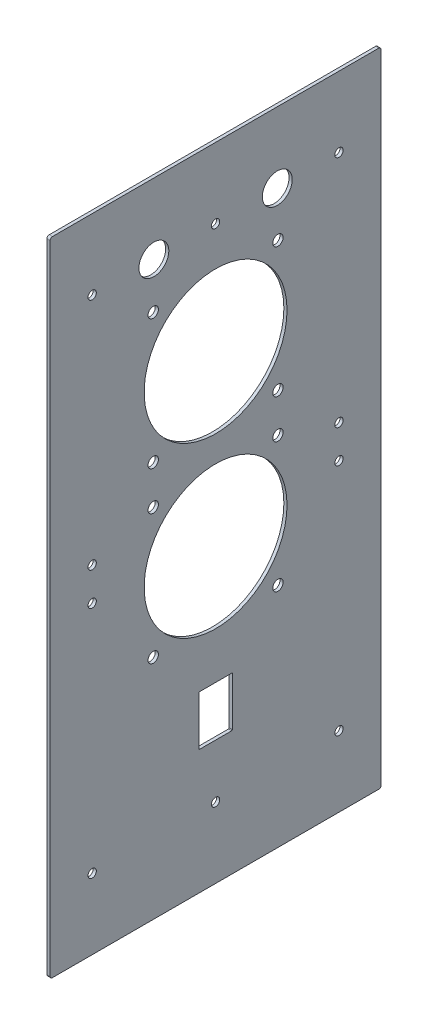
SolidWorks part; units mm, degrees
material "AISI 1020 Steel, Cold Rolled"
ref_plane "Front Plane" through (0, 0, 0) normal (0, 0, 1) x (1, 0, 0)
ref_plane "Top Plane" through (0, 0, 0) normal (0, 1, 0) x (1, 0, 0)
ref_plane "Right Plane" through (0, 0, 0) normal (1, 0, 0) x (0, 0, -1)
sketch "Sketch1" plane through (0, 0, 0) normal (1, 0, 0) x (0, 0, -1)
  line L0 (-62.8, -237.66) -> (62.8, -237.66) construction
  line L1 (-62.8, 9.9) -> (62.8, 9.9) construction
  line L2 (-62.8, -237.66) -> (62.8, -237.66) construction
  line L3 (-62.8, 9.9) -> (62.8, 9.9) construction
  line L4 (-63.943, 8.757) -> (-63.943, -236.517) construction
  line L5 (63.943, -236.517) -> (63.943, 8.757) construction
  line L6 (-62.8, 9.646) -> (62.8, 9.646)
  line L7 (63.689, -236.517) -> (63.689, 8.757)
  line L8 (-62.8, -237.406) -> (62.8, -237.406)
  line L9 (-63.689, 8.757) -> (-63.689, -236.517)
  arc A0 (63.943, 8.757) -> (62.8, 9.9) centre (62.8, 8.757) ccw construction
  arc A1 (62.8, -237.66) -> (63.943, -236.517) centre (62.8, -236.517) ccw construction
  arc A2 (-63.943, -236.517) -> (-62.8, -237.66) centre (-62.8, -236.517) ccw construction
  arc A3 (-62.8, 9.9) -> (-63.943, 8.757) centre (-62.8, 8.757) ccw construction
  arc A4 (63.943, 8.757) -> (62.8, 9.9) centre (62.8, 8.757) ccw construction
  arc A5 (62.8, -237.66) -> (63.943, -236.517) centre (62.8, -236.517) ccw construction
  arc A6 (-63.943, -236.517) -> (-62.8, -237.66) centre (-62.8, -236.517) ccw construction
  arc A7 (-62.8, 9.9) -> (-63.943, 8.757) centre (-62.8, 8.757) ccw construction
  arc A8 (63.689, 8.757) -> (62.8, 9.646) centre (62.8, 8.757) ccw
  arc A9 (62.8, -237.406) -> (63.689, -236.517) centre (62.8, -236.517) ccw
  arc A10 (-63.689, -236.517) -> (-62.8, -237.406) centre (-62.8, -236.517) ccw
  arc A11 (-62.8, 9.646) -> (-63.689, 8.757) centre (-62.8, 8.757) ccw
  dimension "D1" = 0.254
extrude "Boss-Extrude1" add sketch "Sketch1" along normal blind 1.22 contours L6 A11 L9 A10 L8 A9 L7 A8
sketch "Sketch2" plane through (0, 0, 0) normal (1, 0, 0) x (0, 0, -1)
  line L0 (0, 9.646) -> (0, -237.406) construction
  line L1 (-62.8, 9.646) -> (62.8, 9.646) construction
  line L2 (-62.8, -237.406) -> (62.8, -237.406) construction
  line L3 (0, -10.38) -> (0, 6.62) construction
  line L4 (-1.5, -10.38) -> (-1.5, 6.62)
  line L5 (1.5, -10.38) -> (1.5, 6.62)
  line L6 (0, -113.88) -> (80.3915, -113.88) construction
  line L7 (10, -10.38) -> (10, 6.62) construction
  line L8 (8.5, -10.38) -> (8.5, 6.62)
  line L9 (11.5, -10.38) -> (11.5, 6.62)
  line L10 (20, -10.38) -> (20, 6.62) construction
  line L11 (18.5, -10.38) -> (18.5, 6.62)
  line L12 (21.5, -10.38) -> (21.5, 6.62)
  line L13 (30, -10.38) -> (30, 6.62) construction
  line L14 (28.5, -10.38) -> (28.5, 6.62)
  line L15 (31.5, -10.38) -> (31.5, 6.62)
  line L16 (40, -10.38) -> (40, 6.62) construction
  line L17 (38.5, -10.38) -> (38.5, 6.62)
  line L18 (41.5, -10.38) -> (41.5, 6.62)
  line L19 (50, -10.38) -> (50, 6.62) construction
  line L20 (48.5, -10.38) -> (48.5, 6.62)
  line L21 (51.5, -10.38) -> (51.5, 6.62)
  line L22 (0, -10.38) -> (0, 6.62) construction
  line L23 (-1.5, -10.38) -> (-1.5, 6.62)
  line L24 (1.5, -10.38) -> (1.5, 6.62)
  line L25 (10, -10.38) -> (10, 6.62) construction
  line L26 (8.5, -10.38) -> (8.5, 6.62)
  line L27 (11.5, -10.38) -> (11.5, 6.62)
  line L28 (20, -10.38) -> (20, 6.62) construction
  line L29 (18.5, -10.38) -> (18.5, 6.62)
  line L30 (21.5, -10.38) -> (21.5, 6.62)
  line L31 (30, -10.38) -> (30, 6.62) construction
  line L32 (28.5, -10.38) -> (28.5, 6.62)
  line L33 (31.5, -10.38) -> (31.5, 6.62)
  line L34 (40, -10.38) -> (40, 6.62) construction
  line L35 (38.5, -10.38) -> (38.5, 6.62)
  line L36 (41.5, -10.38) -> (41.5, 6.62)
  line L37 (-10, -10.38) -> (-10, 6.62) construction
  line L38 (-11.5, -10.38) -> (-11.5, 6.62)
  line L39 (-8.5, -10.38) -> (-8.5, 6.62)
  line L40 (0, -10.38) -> (0, 6.62) construction
  line L41 (-1.5, -10.38) -> (-1.5, 6.62)
  line L42 (1.5, -10.38) -> (1.5, 6.62)
  line L43 (10, -10.38) -> (10, 6.62) construction
  line L44 (8.5, -10.38) -> (8.5, 6.62)
  line L45 (11.5, -10.38) -> (11.5, 6.62)
  line L46 (20, -10.38) -> (20, 6.62) construction
  line L47 (18.5, -10.38) -> (18.5, 6.62)
  line L48 (21.5, -10.38) -> (21.5, 6.62)
  line L49 (30, -10.38) -> (30, 6.62) construction
  line L50 (28.5, -10.38) -> (28.5, 6.62)
  line L51 (31.5, -10.38) -> (31.5, 6.62)
  line L52 (-20, -10.38) -> (-20, 6.62) construction
  line L53 (-21.5, -10.38) -> (-21.5, 6.62)
  line L54 (-18.5, -10.38) -> (-18.5, 6.62)
  line L55 (-10, -10.38) -> (-10, 6.62) construction
  line L56 (-11.5, -10.38) -> (-11.5, 6.62)
  line L57 (-8.5, -10.38) -> (-8.5, 6.62)
  line L58 (0, -10.38) -> (0, 6.62) construction
  line L59 (-1.5, -10.38) -> (-1.5, 6.62)
  line L60 (1.5, -10.38) -> (1.5, 6.62)
  line L61 (10, -10.38) -> (10, 6.62) construction
  line L62 (8.5, -10.38) -> (8.5, 6.62)
  line L63 (11.5, -10.38) -> (11.5, 6.62)
  line L64 (20, -10.38) -> (20, 6.62) construction
  line L65 (18.5, -10.38) -> (18.5, 6.62)
  line L66 (21.5, -10.38) -> (21.5, 6.62)
  line L67 (-30, -10.38) -> (-30, 6.62) construction
  line L68 (-31.5, -10.38) -> (-31.5, 6.62)
  line L69 (-28.5, -10.38) -> (-28.5, 6.62)
  line L70 (-20, -10.38) -> (-20, 6.62) construction
  line L71 (-21.5, -10.38) -> (-21.5, 6.62)
  line L72 (-18.5, -10.38) -> (-18.5, 6.62)
  line L73 (-10, -10.38) -> (-10, 6.62) construction
  line L74 (-11.5, -10.38) -> (-11.5, 6.62)
  line L75 (-8.5, -10.38) -> (-8.5, 6.62)
  line L76 (0, -10.38) -> (0, 6.62) construction
  line L77 (-1.5, -10.38) -> (-1.5, 6.62)
  line L78 (1.5, -10.38) -> (1.5, 6.62)
  line L79 (10, -10.38) -> (10, 6.62) construction
  line L80 (8.5, -10.38) -> (8.5, 6.62)
  line L81 (11.5, -10.38) -> (11.5, 6.62)
  line L82 (-40, -10.38) -> (-40, 6.62) construction
  line L83 (-41.5, -10.38) -> (-41.5, 6.62)
  line L84 (-38.5, -10.38) -> (-38.5, 6.62)
  line L85 (-30, -10.38) -> (-30, 6.62) construction
  line L86 (-31.5, -10.38) -> (-31.5, 6.62)
  line L87 (-28.5, -10.38) -> (-28.5, 6.62)
  line L88 (-20, -10.38) -> (-20, 6.62) construction
  line L89 (-21.5, -10.38) -> (-21.5, 6.62)
  line L90 (-18.5, -10.38) -> (-18.5, 6.62)
  line L91 (-10, -10.38) -> (-10, 6.62) construction
  line L92 (-11.5, -10.38) -> (-11.5, 6.62)
  line L93 (-8.5, -10.38) -> (-8.5, 6.62)
  line L94 (0, -10.38) -> (0, 6.62) construction
  line L95 (-1.5, -10.38) -> (-1.5, 6.62)
  line L96 (1.5, -10.38) -> (1.5, 6.62)
  line L97 (-10, -10.38) -> (-10, 6.62) construction
  line L98 (-11.5, -10.38) -> (-11.5, 6.62)
  line L99 (-8.5, -10.38) -> (-8.5, 6.62)
  line L100 (-20, -10.38) -> (-20, 6.62) construction
  line L101 (-21.5, -10.38) -> (-21.5, 6.62)
  line L102 (-18.5, -10.38) -> (-18.5, 6.62)
  line L103 (-30, -10.38) -> (-30, 6.62) construction
  line L104 (-31.5, -10.38) -> (-31.5, 6.62)
  line L105 (-28.5, -10.38) -> (-28.5, 6.62)
  line L106 (-40, -10.38) -> (-40, 6.62) construction
  line L107 (-41.5, -10.38) -> (-41.5, 6.62)
  line L108 (-38.5, -10.38) -> (-38.5, 6.62)
  line L109 (-50, -10.38) -> (-50, 6.62) construction
  line L110 (-51.5, -10.38) -> (-51.5, 6.62)
  line L111 (-48.5, -10.38) -> (-48.5, 6.62)
  line L112 (0, -217.38) -> (0, -234.38) construction
  line L113 (-1.5, -217.38) -> (-1.5, -234.38)
  line L114 (1.5, -217.38) -> (1.5, -234.38)
  line L115 (10, -217.38) -> (10, -234.38) construction
  line L116 (8.5, -217.38) -> (8.5, -234.38)
  line L117 (11.5, -217.38) -> (11.5, -234.38)
  line L118 (20, -217.38) -> (20, -234.38) construction
  line L119 (18.5, -217.38) -> (18.5, -234.38)
  line L120 (21.5, -217.38) -> (21.5, -234.38)
  line L121 (30, -217.38) -> (30, -234.38) construction
  line L122 (28.5, -217.38) -> (28.5, -234.38)
  line L123 (31.5, -217.38) -> (31.5, -234.38)
  line L124 (40, -217.38) -> (40, -234.38) construction
  line L125 (38.5, -217.38) -> (38.5, -234.38)
  line L126 (41.5, -217.38) -> (41.5, -234.38)
  line L127 (50, -217.38) -> (50, -234.38) construction
  line L128 (48.5, -217.38) -> (48.5, -234.38)
  line L129 (51.5, -217.38) -> (51.5, -234.38)
  line L130 (0, -217.38) -> (0, -234.38) construction
  line L131 (-1.5, -217.38) -> (-1.5, -234.38)
  line L132 (1.5, -217.38) -> (1.5, -234.38)
  line L133 (10, -217.38) -> (10, -234.38) construction
  line L134 (8.5, -217.38) -> (8.5, -234.38)
  line L135 (11.5, -217.38) -> (11.5, -234.38)
  line L136 (20, -217.38) -> (20, -234.38) construction
  line L137 (18.5, -217.38) -> (18.5, -234.38)
  line L138 (21.5, -217.38) -> (21.5, -234.38)
  line L139 (30, -217.38) -> (30, -234.38) construction
  line L140 (28.5, -217.38) -> (28.5, -234.38)
  line L141 (31.5, -217.38) -> (31.5, -234.38)
  line L142 (40, -217.38) -> (40, -234.38) construction
  line L143 (38.5, -217.38) -> (38.5, -234.38)
  line L144 (41.5, -217.38) -> (41.5, -234.38)
  line L145 (-10, -217.38) -> (-10, -234.38) construction
  line L146 (-11.5, -217.38) -> (-11.5, -234.38)
  line L147 (-8.5, -217.38) -> (-8.5, -234.38)
  line L148 (0, -217.38) -> (0, -234.38) construction
  line L149 (-1.5, -217.38) -> (-1.5, -234.38)
  line L150 (1.5, -217.38) -> (1.5, -234.38)
  line L151 (10, -217.38) -> (10, -234.38) construction
  line L152 (8.5, -217.38) -> (8.5, -234.38)
  line L153 (11.5, -217.38) -> (11.5, -234.38)
  line L154 (20, -217.38) -> (20, -234.38) construction
  line L155 (18.5, -217.38) -> (18.5, -234.38)
  line L156 (21.5, -217.38) -> (21.5, -234.38)
  line L157 (30, -217.38) -> (30, -234.38) construction
  line L158 (28.5, -217.38) -> (28.5, -234.38)
  line L159 (31.5, -217.38) -> (31.5, -234.38)
  line L160 (-20, -217.38) -> (-20, -234.38) construction
  line L161 (-21.5, -217.38) -> (-21.5, -234.38)
  line L162 (-18.5, -217.38) -> (-18.5, -234.38)
  line L163 (-10, -217.38) -> (-10, -234.38) construction
  line L164 (-11.5, -217.38) -> (-11.5, -234.38)
  line L165 (-8.5, -217.38) -> (-8.5, -234.38)
  line L166 (0, -217.38) -> (0, -234.38) construction
  line L167 (-1.5, -217.38) -> (-1.5, -234.38)
  line L168 (1.5, -217.38) -> (1.5, -234.38)
  line L169 (10, -217.38) -> (10, -234.38) construction
  line L170 (8.5, -217.38) -> (8.5, -234.38)
  line L171 (11.5, -217.38) -> (11.5, -234.38)
  line L172 (20, -217.38) -> (20, -234.38) construction
  line L173 (18.5, -217.38) -> (18.5, -234.38)
  line L174 (21.5, -217.38) -> (21.5, -234.38)
  line L175 (-30, -217.38) -> (-30, -234.38) construction
  line L176 (-31.5, -217.38) -> (-31.5, -234.38)
  line L177 (-28.5, -217.38) -> (-28.5, -234.38)
  line L178 (-20, -217.38) -> (-20, -234.38) construction
  line L179 (-21.5, -217.38) -> (-21.5, -234.38)
  line L180 (-18.5, -217.38) -> (-18.5, -234.38)
  line L181 (-10, -217.38) -> (-10, -234.38) construction
  line L182 (-11.5, -217.38) -> (-11.5, -234.38)
  line L183 (-8.5, -217.38) -> (-8.5, -234.38)
  line L184 (0, -217.38) -> (0, -234.38) construction
  line L185 (-1.5, -217.38) -> (-1.5, -234.38)
  line L186 (1.5, -217.38) -> (1.5, -234.38)
  line L187 (10, -217.38) -> (10, -234.38) construction
  line L188 (8.5, -217.38) -> (8.5, -234.38)
  line L189 (11.5, -217.38) -> (11.5, -234.38)
  line L190 (-40, -217.38) -> (-40, -234.38) construction
  line L191 (-41.5, -217.38) -> (-41.5, -234.38)
  line L192 (-38.5, -217.38) -> (-38.5, -234.38)
  line L193 (-30, -217.38) -> (-30, -234.38) construction
  line L194 (-31.5, -217.38) -> (-31.5, -234.38)
  line L195 (-28.5, -217.38) -> (-28.5, -234.38)
  line L196 (-20, -217.38) -> (-20, -234.38) construction
  line L197 (-21.5, -217.38) -> (-21.5, -234.38)
  line L198 (-18.5, -217.38) -> (-18.5, -234.38)
  line L199 (-10, -217.38) -> (-10, -234.38) construction
  line L200 (-11.5, -217.38) -> (-11.5, -234.38)
  line L201 (-8.5, -217.38) -> (-8.5, -234.38)
  line L202 (0, -217.38) -> (0, -234.38) construction
  line L203 (-1.5, -217.38) -> (-1.5, -234.38)
  line L204 (1.5, -217.38) -> (1.5, -234.38)
  line L205 (-10, -217.38) -> (-10, -234.38) construction
  line L206 (-11.5, -217.38) -> (-11.5, -234.38)
  line L207 (-8.5, -217.38) -> (-8.5, -234.38)
  line L208 (-20, -217.38) -> (-20, -234.38) construction
  line L209 (-21.5, -217.38) -> (-21.5, -234.38)
  line L210 (-18.5, -217.38) -> (-18.5, -234.38)
  line L211 (-30, -217.38) -> (-30, -234.38) construction
  line L212 (-31.5, -217.38) -> (-31.5, -234.38)
  line L213 (-28.5, -217.38) -> (-28.5, -234.38)
  line L214 (-40, -217.38) -> (-40, -234.38) construction
  line L215 (-41.5, -217.38) -> (-41.5, -234.38)
  line L216 (-38.5, -217.38) -> (-38.5, -234.38)
  line L217 (-50, -217.38) -> (-50, -234.38) construction
  line L218 (-51.5, -217.38) -> (-51.5, -234.38)
  line L219 (-48.5, -217.38) -> (-48.5, -234.38)
  arc A0 (-1.5, -10.38) -> (1.5, -10.38) centre (0, -10.38) ccw
  arc A1 (1.5, 6.62) -> (-1.5, 6.62) centre (0, 6.62) ccw
  arc A2 (8.5, -10.38) -> (11.5, -10.38) centre (10, -10.38) ccw
  arc A3 (11.5, 6.62) -> (8.5, 6.62) centre (10, 6.62) ccw
  arc A4 (18.5, -10.38) -> (21.5, -10.38) centre (20, -10.38) ccw
  arc A5 (21.5, 6.62) -> (18.5, 6.62) centre (20, 6.62) ccw
  arc A6 (28.5, -10.38) -> (31.5, -10.38) centre (30, -10.38) ccw
  arc A7 (31.5, 6.62) -> (28.5, 6.62) centre (30, 6.62) ccw
  arc A8 (38.5, -10.38) -> (41.5, -10.38) centre (40, -10.38) ccw
  arc A9 (41.5, 6.62) -> (38.5, 6.62) centre (40, 6.62) ccw
  arc A10 (48.5, -10.38) -> (51.5, -10.38) centre (50, -10.38) ccw
  arc A11 (51.5, 6.62) -> (48.5, 6.62) centre (50, 6.62) ccw
  arc A12 (-1.5, -10.38) -> (1.5, -10.38) centre (0, -10.38) ccw
  arc A13 (1.5, 6.62) -> (-1.5, 6.62) centre (0, 6.62) ccw
  arc A14 (8.5, -10.38) -> (11.5, -10.38) centre (10, -10.38) ccw
  arc A15 (11.5, 6.62) -> (8.5, 6.62) centre (10, 6.62) ccw
  arc A16 (18.5, -10.38) -> (21.5, -10.38) centre (20, -10.38) ccw
  arc A17 (21.5, 6.62) -> (18.5, 6.62) centre (20, 6.62) ccw
  arc A18 (28.5, -10.38) -> (31.5, -10.38) centre (30, -10.38) ccw
  arc A19 (31.5, 6.62) -> (28.5, 6.62) centre (30, 6.62) ccw
  arc A20 (38.5, -10.38) -> (41.5, -10.38) centre (40, -10.38) ccw
  arc A21 (41.5, 6.62) -> (38.5, 6.62) centre (40, 6.62) ccw
  arc A22 (-11.5, -10.38) -> (-8.5, -10.38) centre (-10, -10.38) ccw
  arc A23 (-8.5, 6.62) -> (-11.5, 6.62) centre (-10, 6.62) ccw
  arc A24 (-1.5, -10.38) -> (1.5, -10.38) centre (0, -10.38) ccw
  arc A25 (1.5, 6.62) -> (-1.5, 6.62) centre (0, 6.62) ccw
  arc A26 (8.5, -10.38) -> (11.5, -10.38) centre (10, -10.38) ccw
  arc A27 (11.5, 6.62) -> (8.5, 6.62) centre (10, 6.62) ccw
  arc A28 (18.5, -10.38) -> (21.5, -10.38) centre (20, -10.38) ccw
  arc A29 (21.5, 6.62) -> (18.5, 6.62) centre (20, 6.62) ccw
  arc A30 (28.5, -10.38) -> (31.5, -10.38) centre (30, -10.38) ccw
  arc A31 (31.5, 6.62) -> (28.5, 6.62) centre (30, 6.62) ccw
  arc A32 (-21.5, -10.38) -> (-18.5, -10.38) centre (-20, -10.38) ccw
  arc A33 (-18.5, 6.62) -> (-21.5, 6.62) centre (-20, 6.62) ccw
  arc A34 (-11.5, -10.38) -> (-8.5, -10.38) centre (-10, -10.38) ccw
  arc A35 (-8.5, 6.62) -> (-11.5, 6.62) centre (-10, 6.62) ccw
  arc A36 (-1.5, -10.38) -> (1.5, -10.38) centre (0, -10.38) ccw
  arc A37 (1.5, 6.62) -> (-1.5, 6.62) centre (0, 6.62) ccw
  arc A38 (8.5, -10.38) -> (11.5, -10.38) centre (10, -10.38) ccw
  arc A39 (11.5, 6.62) -> (8.5, 6.62) centre (10, 6.62) ccw
  arc A40 (18.5, -10.38) -> (21.5, -10.38) centre (20, -10.38) ccw
  arc A41 (21.5, 6.62) -> (18.5, 6.62) centre (20, 6.62) ccw
  arc A42 (-31.5, -10.38) -> (-28.5, -10.38) centre (-30, -10.38) ccw
  arc A43 (-28.5, 6.62) -> (-31.5, 6.62) centre (-30, 6.62) ccw
  arc A44 (-21.5, -10.38) -> (-18.5, -10.38) centre (-20, -10.38) ccw
  arc A45 (-18.5, 6.62) -> (-21.5, 6.62) centre (-20, 6.62) ccw
  arc A46 (-11.5, -10.38) -> (-8.5, -10.38) centre (-10, -10.38) ccw
  arc A47 (-8.5, 6.62) -> (-11.5, 6.62) centre (-10, 6.62) ccw
  arc A48 (-1.5, -10.38) -> (1.5, -10.38) centre (0, -10.38) ccw
  arc A49 (1.5, 6.62) -> (-1.5, 6.62) centre (0, 6.62) ccw
  arc A50 (8.5, -10.38) -> (11.5, -10.38) centre (10, -10.38) ccw
  arc A51 (11.5, 6.62) -> (8.5, 6.62) centre (10, 6.62) ccw
  arc A52 (-41.5, -10.38) -> (-38.5, -10.38) centre (-40, -10.38) ccw
  arc A53 (-38.5, 6.62) -> (-41.5, 6.62) centre (-40, 6.62) ccw
  arc A54 (-31.5, -10.38) -> (-28.5, -10.38) centre (-30, -10.38) ccw
  arc A55 (-28.5, 6.62) -> (-31.5, 6.62) centre (-30, 6.62) ccw
  arc A56 (-21.5, -10.38) -> (-18.5, -10.38) centre (-20, -10.38) ccw
  arc A57 (-18.5, 6.62) -> (-21.5, 6.62) centre (-20, 6.62) ccw
  arc A58 (-11.5, -10.38) -> (-8.5, -10.38) centre (-10, -10.38) ccw
  arc A59 (-8.5, 6.62) -> (-11.5, 6.62) centre (-10, 6.62) ccw
  arc A60 (-1.5, -10.38) -> (1.5, -10.38) centre (0, -10.38) ccw
  arc A61 (1.5, 6.62) -> (-1.5, 6.62) centre (0, 6.62) ccw
  arc A62 (-11.5, -10.38) -> (-8.5, -10.38) centre (-10, -10.38) ccw
  arc A63 (-8.5, 6.62) -> (-11.5, 6.62) centre (-10, 6.62) ccw
  arc A64 (-21.5, -10.38) -> (-18.5, -10.38) centre (-20, -10.38) ccw
  arc A65 (-18.5, 6.62) -> (-21.5, 6.62) centre (-20, 6.62) ccw
  arc A66 (-31.5, -10.38) -> (-28.5, -10.38) centre (-30, -10.38) ccw
  arc A67 (-28.5, 6.62) -> (-31.5, 6.62) centre (-30, 6.62) ccw
  arc A68 (-41.5, -10.38) -> (-38.5, -10.38) centre (-40, -10.38) ccw
  arc A69 (-38.5, 6.62) -> (-41.5, 6.62) centre (-40, 6.62) ccw
  arc A70 (-51.5, -10.38) -> (-48.5, -10.38) centre (-50, -10.38) ccw
  arc A71 (-48.5, 6.62) -> (-51.5, 6.62) centre (-50, 6.62) ccw
  arc A72 (-1.5, -217.38) -> (1.5, -217.38) centre (0, -217.38) cw
  arc A73 (1.5, -234.38) -> (-1.5, -234.38) centre (0, -234.38) cw
  arc A74 (8.5, -217.38) -> (11.5, -217.38) centre (10, -217.38) cw
  arc A75 (11.5, -234.38) -> (8.5, -234.38) centre (10, -234.38) cw
  arc A76 (18.5, -217.38) -> (21.5, -217.38) centre (20, -217.38) cw
  arc A77 (21.5, -234.38) -> (18.5, -234.38) centre (20, -234.38) cw
  arc A78 (28.5, -217.38) -> (31.5, -217.38) centre (30, -217.38) cw
  arc A79 (31.5, -234.38) -> (28.5, -234.38) centre (30, -234.38) cw
  arc A80 (38.5, -217.38) -> (41.5, -217.38) centre (40, -217.38) cw
  arc A81 (41.5, -234.38) -> (38.5, -234.38) centre (40, -234.38) cw
  arc A82 (48.5, -217.38) -> (51.5, -217.38) centre (50, -217.38) cw
  arc A83 (51.5, -234.38) -> (48.5, -234.38) centre (50, -234.38) cw
  arc A84 (-1.5, -217.38) -> (1.5, -217.38) centre (0, -217.38) cw
  arc A85 (1.5, -234.38) -> (-1.5, -234.38) centre (0, -234.38) cw
  arc A86 (8.5, -217.38) -> (11.5, -217.38) centre (10, -217.38) cw
  arc A87 (11.5, -234.38) -> (8.5, -234.38) centre (10, -234.38) cw
  arc A88 (18.5, -217.38) -> (21.5, -217.38) centre (20, -217.38) cw
  arc A89 (21.5, -234.38) -> (18.5, -234.38) centre (20, -234.38) cw
  arc A90 (28.5, -217.38) -> (31.5, -217.38) centre (30, -217.38) cw
  arc A91 (31.5, -234.38) -> (28.5, -234.38) centre (30, -234.38) cw
  arc A92 (38.5, -217.38) -> (41.5, -217.38) centre (40, -217.38) cw
  arc A93 (41.5, -234.38) -> (38.5, -234.38) centre (40, -234.38) cw
  arc A94 (-11.5, -217.38) -> (-8.5, -217.38) centre (-10, -217.38) cw
  arc A95 (-8.5, -234.38) -> (-11.5, -234.38) centre (-10, -234.38) cw
  arc A96 (-1.5, -217.38) -> (1.5, -217.38) centre (0, -217.38) cw
  arc A97 (1.5, -234.38) -> (-1.5, -234.38) centre (0, -234.38) cw
  arc A98 (8.5, -217.38) -> (11.5, -217.38) centre (10, -217.38) cw
  arc A99 (11.5, -234.38) -> (8.5, -234.38) centre (10, -234.38) cw
  arc A100 (18.5, -217.38) -> (21.5, -217.38) centre (20, -217.38) cw
  arc A101 (21.5, -234.38) -> (18.5, -234.38) centre (20, -234.38) cw
  arc A102 (28.5, -217.38) -> (31.5, -217.38) centre (30, -217.38) cw
  arc A103 (31.5, -234.38) -> (28.5, -234.38) centre (30, -234.38) cw
  arc A104 (-21.5, -217.38) -> (-18.5, -217.38) centre (-20, -217.38) cw
  arc A105 (-18.5, -234.38) -> (-21.5, -234.38) centre (-20, -234.38) cw
  arc A106 (-11.5, -217.38) -> (-8.5, -217.38) centre (-10, -217.38) cw
  arc A107 (-8.5, -234.38) -> (-11.5, -234.38) centre (-10, -234.38) cw
  arc A108 (-1.5, -217.38) -> (1.5, -217.38) centre (0, -217.38) cw
  arc A109 (1.5, -234.38) -> (-1.5, -234.38) centre (0, -234.38) cw
  arc A110 (8.5, -217.38) -> (11.5, -217.38) centre (10, -217.38) cw
  arc A111 (11.5, -234.38) -> (8.5, -234.38) centre (10, -234.38) cw
  arc A112 (18.5, -217.38) -> (21.5, -217.38) centre (20, -217.38) cw
  arc A113 (21.5, -234.38) -> (18.5, -234.38) centre (20, -234.38) cw
  arc A114 (-31.5, -217.38) -> (-28.5, -217.38) centre (-30, -217.38) cw
  arc A115 (-28.5, -234.38) -> (-31.5, -234.38) centre (-30, -234.38) cw
  arc A116 (-21.5, -217.38) -> (-18.5, -217.38) centre (-20, -217.38) cw
  arc A117 (-18.5, -234.38) -> (-21.5, -234.38) centre (-20, -234.38) cw
  arc A118 (-11.5, -217.38) -> (-8.5, -217.38) centre (-10, -217.38) cw
  arc A119 (-8.5, -234.38) -> (-11.5, -234.38) centre (-10, -234.38) cw
  arc A120 (-1.5, -217.38) -> (1.5, -217.38) centre (0, -217.38) cw
  arc A121 (1.5, -234.38) -> (-1.5, -234.38) centre (0, -234.38) cw
  arc A122 (8.5, -217.38) -> (11.5, -217.38) centre (10, -217.38) cw
  arc A123 (11.5, -234.38) -> (8.5, -234.38) centre (10, -234.38) cw
  arc A124 (-41.5, -217.38) -> (-38.5, -217.38) centre (-40, -217.38) cw
  arc A125 (-38.5, -234.38) -> (-41.5, -234.38) centre (-40, -234.38) cw
  arc A126 (-31.5, -217.38) -> (-28.5, -217.38) centre (-30, -217.38) cw
  arc A127 (-28.5, -234.38) -> (-31.5, -234.38) centre (-30, -234.38) cw
  arc A128 (-21.5, -217.38) -> (-18.5, -217.38) centre (-20, -217.38) cw
  arc A129 (-18.5, -234.38) -> (-21.5, -234.38) centre (-20, -234.38) cw
  arc A130 (-11.5, -217.38) -> (-8.5, -217.38) centre (-10, -217.38) cw
  arc A131 (-8.5, -234.38) -> (-11.5, -234.38) centre (-10, -234.38) cw
  arc A132 (-1.5, -217.38) -> (1.5, -217.38) centre (0, -217.38) cw
  arc A133 (1.5, -234.38) -> (-1.5, -234.38) centre (0, -234.38) cw
  arc A134 (-11.5, -217.38) -> (-8.5, -217.38) centre (-10, -217.38) cw
  arc A135 (-8.5, -234.38) -> (-11.5, -234.38) centre (-10, -234.38) cw
  arc A136 (-21.5, -217.38) -> (-18.5, -217.38) centre (-20, -217.38) cw
  arc A137 (-18.5, -234.38) -> (-21.5, -234.38) centre (-20, -234.38) cw
  arc A138 (-31.5, -217.38) -> (-28.5, -217.38) centre (-30, -217.38) cw
  arc A139 (-28.5, -234.38) -> (-31.5, -234.38) centre (-30, -234.38) cw
  arc A140 (-41.5, -217.38) -> (-38.5, -217.38) centre (-40, -217.38) cw
  arc A141 (-38.5, -234.38) -> (-41.5, -234.38) centre (-40, -234.38) cw
  arc A142 (-51.5, -217.38) -> (-48.5, -217.38) centre (-50, -217.38) cw
  arc A143 (-48.5, -234.38) -> (-51.5, -234.38) centre (-50, -234.38) cw
  point P6 (0, -1.88)
  point P16 (0, -225.88)
  point P20 (10, -1.88)
  point P27 (20, -1.88)
  point P34 (30, -1.88)
  point P41 (40, -1.88)
  point P48 (50, -1.88)
  point P55 (0, -1.88)
  point P62 (10, -1.88)
  point P69 (20, -1.88)
  point P76 (30, -1.88)
  point P83 (40, -1.88)
  point P90 (-10, -1.88)
  point P97 (0, -1.88)
  point P104 (10, -1.88)
  point P111 (20, -1.88)
  point P118 (30, -1.88)
  point P125 (-20, -1.88)
  point P132 (-10, -1.88)
  point P139 (0, -1.88)
  point P146 (10, -1.88)
  point P153 (20, -1.88)
  point P160 (-30, -1.88)
  point P167 (-20, -1.88)
  point P174 (-10, -1.88)
  point P181 (0, -1.88)
  point P188 (10, -1.88)
  point P195 (-40, -1.88)
  point P202 (-30, -1.88)
  point P209 (-20, -1.88)
  point P216 (-10, -1.88)
  point P223 (0, -1.88)
  point P230 (-10, -1.88)
  point P237 (-20, -1.88)
  point P244 (-30, -1.88)
  point P251 (-40, -1.88)
  point P258 (-50, -1.88)
  point P270 (10, -225.88)
  point P277 (20, -225.88)
  point P284 (30, -225.88)
  point P291 (40, -225.88)
  point P298 (50, -225.88)
  point P305 (0, -225.88)
  point P312 (10, -225.88)
  point P319 (20, -225.88)
  point P326 (30, -225.88)
  point P333 (40, -225.88)
  point P340 (-10, -225.88)
  point P347 (0, -225.88)
  point P354 (10, -225.88)
  point P361 (20, -225.88)
  point P368 (30, -225.88)
  point P375 (-20, -225.88)
  point P382 (-10, -225.88)
  point P389 (0, -225.88)
  point P396 (10, -225.88)
  point P403 (20, -225.88)
  point P410 (-30, -225.88)
  point P417 (-20, -225.88)
  point P424 (-10, -225.88)
  point P431 (0, -225.88)
  point P438 (10, -225.88)
  point P445 (-40, -225.88)
  point P452 (-30, -225.88)
  point P459 (-20, -225.88)
  point P466 (-10, -225.88)
  point P473 (0, -225.88)
  point P480 (-10, -225.88)
  point P487 (-20, -225.88)
  point P494 (-30, -225.88)
  point P501 (-40, -225.88)
  point P508 (-50, -225.88)
  dimension "D2" = 20
  dimension "D1" = 3
  dimension "D3" = 112
  dimension "D4" = 6
  dimension "D5" = 6
extrude "Cut-Extrude1" [suppressed] cut sketch "Sketch2" against normal through all and the other way through all contours L21 A11 L20 A10 | L18 A9 L17 A8 | L15 A7 L14 A6 | L12 A5 L11 A4 | L9 A3 L8 A2 | L5 A1 L4 A0 | L39 A23 L38 A22 | L54 A33 L53 A32 | L69 A43 L68 A42 | L84 A53 L83 A52 | L111 A71 L110 A70 | L219 A143 L218 A142 | L192 A125 L191 A124 | L177 A115 L176 A114 | L162 A105 L161 A104 | L147 A95 L146 A94 | L114 A73 L113 A72 | L117 A75 L116 A74 | L120 A77 L119 A76 | L123 A79 L122 A78 | L126 A81 L125 A80 | L129 A83 L128 A82
sketch "Sketch5" plane through (0, 0, 0) normal (1, 0, 0) x (0, 0, -1)
  line L0 (-58.82, -113.88) -> (58.82, -113.88) construction
  line L1 (-58.82, -113.88) -> (58.82, -113.88) construction
  circle A0 centre (-47.5, -17.5) radius 1.6
  circle A1 centre (0, -17.5) radius 1.6
  circle A2 centre (47.5, -17.5) radius 1.6
  circle A3 centre (-47.5, -107.5) radius 1.6
  circle A4 centre (47.5, -107.5) radius 1.6
  circle A5 centre (47.5, -120.26) radius 1.6
  circle A6 centre (-47.5, -120.26) radius 1.6
  circle A7 centre (47.5, -210.26) radius 1.6
  circle A8 centre (0, -210.26) radius 1.6
  circle A9 centre (-47.5, -210.26) radius 1.6
  dimension "D1" = 3.2
extrude "Cut-Extrude2" cut sketch "Sketch5" against normal through all and the other way through all
sketch "Sketch6" plane through (0, 0, 0) normal (1, 0, 0) x (0, 0, -1)
  circle A0 centre (0, -60) radius 27.5
  circle A1 centre (0, -125) radius 27.5
  circle A2 centre (24, -35) radius 2
  circle A3 centre (-24, -35) radius 2
  circle A4 centre (-24, -85) radius 2
  circle A5 centre (24, -85) radius 2
  circle A6 centre (24, -100) radius 2
  circle A7 centre (-24, -100) radius 2
  circle A8 centre (-24, -150) radius 2
  circle A9 centre (24, -150) radius 2
  dimension "D1" = 4
  dimension "D2" = 55
extrude "Cut-Extrude3" cut sketch "Sketch6" along normal blind 42
sketch "Sketch7" plane through (0, 0, 0) normal (1, 0, 0) x (0, 0, -1)
  line L0 (-7.05, -169.95) -> (7.05, -190.05) construction
  line L2 (-6.2, -189.6) -> (6.2, -189.6)
  line L3 (-6.45, -189.35) -> (-6.45, -170.65)
  line L4 (-6.2, -170.4) -> (6.2, -170.4)
  line L5 (6.45, -189.35) -> (6.45, -170.65)
  line L6 (-6.45, -189.6) -> (6.45, -170.4) construction
  line L7 (-6.45, -170.4) -> (6.45, -189.6) construction
  arc A0 (6.2, -189.6) -> (6.45, -189.35) centre (6.2, -189.35) ccw
  arc A1 (-6.2, -189.6) -> (-6.45, -189.35) centre (-6.2, -189.35) cw
  arc A2 (6.2, -170.4) -> (6.45, -170.65) centre (6.2, -170.65) cw
  arc A3 (-6.45, -170.65) -> (-6.2, -170.4) centre (-6.2, -170.65) cw
  point P4 (0, -180)
  dimension "D3" = 0.25
  dimension "D1" = 19.2
  dimension "D2" = 12.9
extrude "Cut-Extrude4" cut sketch "Sketch7" along normal through all contours L5 A2 L4 A3 L3 A1 L2 A0
sketch "Sketch8" plane through (1.22, 0, 0) normal (1, 0, 0) x (0, 0, -1)
  circle A0 centre (-23.75, -17.5) radius 5.75
  circle A1 centre (23.75, -17.5) radius 5.75
  dimension "D1" = 11.5
extrude "Cut-Extrude5" cut sketch "Sketch8" against normal through all
